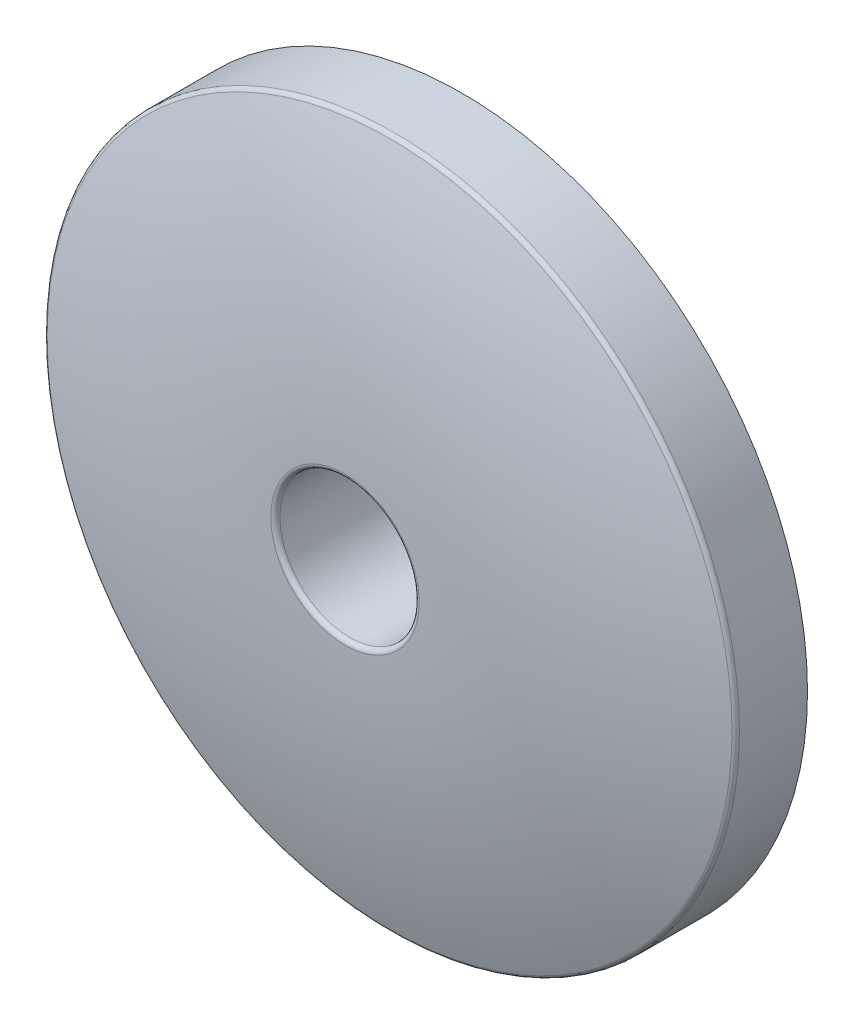
SolidWorks part; units mm, degrees
ref_plane "Front Plane" through (0, 0, 0) normal (0, 0, 1) x (1, 0, 0)
ref_plane "Top Plane" through (0, 0, 0) normal (0, 1, 0) x (1, 0, 0)
ref_plane "Right Plane" through (0, 0, 0) normal (1, 0, 0) x (0, 0, -1)
ref_plane "Plane_axle_y" through (0, -19.05, 0) normal (0, 1, 0) x (1, 0, 0)
sketch "Sk_flange_section" plane through (0, -19.05, 0) normal (0, 1, 0) x (1, 0, 0)
  line L0 (46.228, -7.9375) -> (76.9302, -7.9375)
  line L1 (76.9302, -7.9375) -> (76.9302, -15.5092)
  line L2 (46.228, -20.4445) -> (46.228, -7.9375)
  line L3 (38.481, 50.8) -> (38.481, -50.8) construction
  arc A0 (76.9302, -15.5092) -> (76.5843, -15.9917) centre (76.4197, -15.5084) cw
  arc A1 (76.5843, -15.9917) -> (46.7387, -20.9534) centre (46.228, 74.3636) cw
  arc A2 (46.7387, -20.9534) -> (46.228, -20.4445) centre (46.7354, -20.446) cw
revolve "Rev_flange" add sketch "Sk_flange_section" angle 360 about L3
